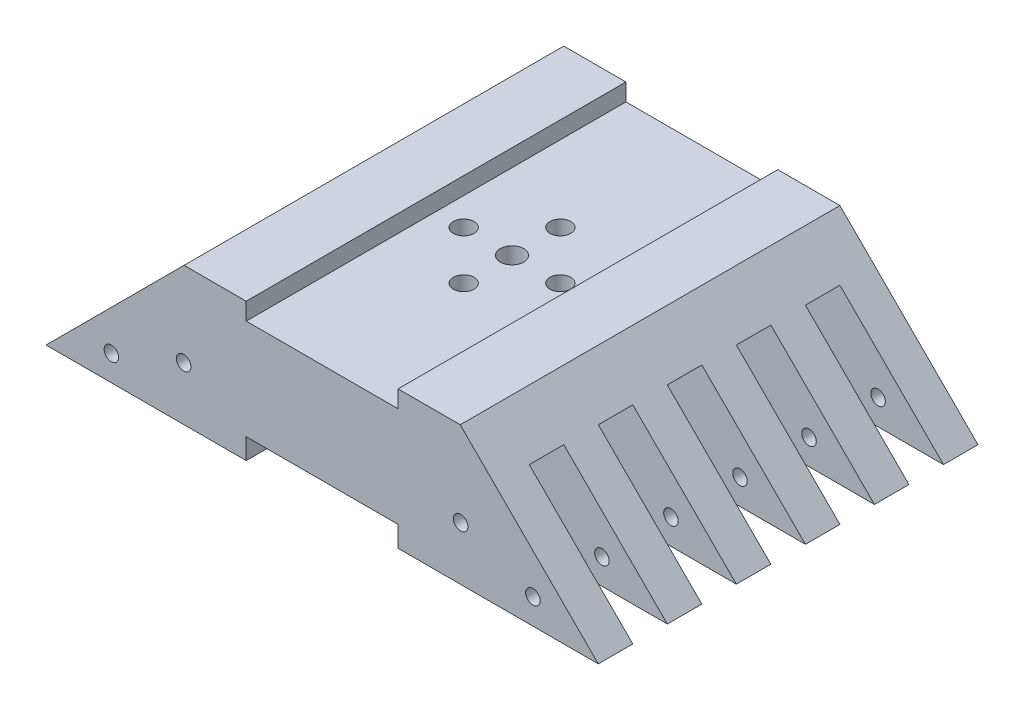
SolidWorks part; units mm, degrees
ref_plane "前视基准面" through (0, 0, 0) normal (0, 0, 1) x (1, 0, 0)
ref_plane "上视基准面" through (0, 0, 0) normal (0, 1, 0) x (1, 0, 0)
ref_plane "右视基准面" through (0, 0, 0) normal (1, 0, 0) x (0, 0, -1)
other "Configuration Table"
sketch "草图1" plane through (0, 0, 0) normal (0, 0, 1) x (1, 0, 0)
  line L0 (-20, 10) -> (20, 10)
  line L1 (-40, -10) -> (40, -10)
  line L2 (-20, 10) -> (-40, -10)
  line L3 (65.6627, -51.1176) -> (66.2035, -49.4794)
  line L4 (20, 10) -> (40, -10)
  line L5 (-11, 10) -> (-11, 7.5)
  line L6 (0, 10) -> (0, -10) construction
  line L7 (11, 10) -> (11, 7.5)
  line L8 (-11, 7.5) -> (11, 7.5)
  line L9 (-11, -10) -> (-11, -7)
  line L10 (11, -10) -> (11, -7)
  line L11 (-11, -7) -> (11, -7)
  line L12 (-20.0626, -2.2419) -> (-40, -10) construction
  circle A0 centre (0, 0) radius 10 construction
  circle A1 centre (-20.0626, -2.2419) radius 1.05
  circle A2 centre (-30.525, -6.3131) radius 1.05
  circle A3 centre (20.0626, -2.2419) radius 1.05
  circle A4 centre (30.525, -6.3131) radius 1.05
  point P6 (0, 10)
  point P9 (0, -10)
  point P29 (0, 0)
  point P30 (-30.525, -6.3131)
  dimension "D1" = 22
  dimension "D6" = 2.1
  dimension "D2" = 40
  dimension "D3" = 80
  dimension "D4" = 2.5
  dimension "D5" = 3
extrude "凸台-拉伸1" add sketch "草图1" along normal blind 55 contours L9 L11 L10 L1 L4 L0 L7 L8 L5 L2
sketch "草图2" plane through (0, -10, 0) normal (0, -1, 0) x (1, 0, 0)
  line L0 (-25.5, 45) -> (-25.5, 40)
  line L1 (-25.5, 55) -> (-25.5, 50)
  line L2 (-40, 55) -> (-11, 55) construction
  line L3 (-25.5, 35) -> (-25.5, 30)
  line L4 (-25.5, 25) -> (-25.5, 20)
  line L5 (-25.5, 15) -> (-25.5, 10)
  line L6 (-25.5, 5) -> (-25.5, 0)
  line L7 (40, 55) -> (40, 0) construction
  line L8 (-40, 55) -> (-40, 0) construction
  line L9 (40, 55) -> (40, 0)
  line L10 (-40, 55) -> (-40, 0)
  line L11 (-40, 50) -> (40, 50)
  line L12 (-40, 45) -> (40, 45)
  line L13 (-40, 40) -> (40, 40)
  line L14 (-40, 35) -> (40, 35)
  line L15 (-40, 30) -> (40, 30)
  line L16 (-40, 25) -> (40, 25)
  line L17 (-40, 20) -> (40, 20)
  line L18 (-40, 15) -> (40, 15)
  line L19 (-40, 10) -> (40, 10)
  line L20 (-40, 5) -> (40, 5)
  line M4 (-11, 0) -> (-11, 55)
  dimension "D1" = 6
  dimension "D2" = 10
extrude "切除-拉伸1" cut sketch "草图2" against normal blind 15 contours L10 L12 L11 M4 | L12 L9 L11 M4 | L10 L14 L13 M4 | L14 L9 L13 M4 | L10 L16 L15 M4 | L16 L9 L15 M4 | L10 L18 L17 M4 | L18 L9 L17 M4 | L10 L20 L19 M4 | L20 L9 L19 M4
sketch "草图3" plane through (0, 7.5, 0) normal (0, 1, 0) x (1, 0, 0)
  line L0 (0, 0) -> (0, -55)
  line L1 (-11, -55) -> (11, -55) construction
  circle A0 centre (0, -27.5) radius 7 construction
  circle A1 centre (0, -20.5) radius 1.5
  circle A2 centre (0, -27.5) radius 1.7
  circle A3 centre (7, -27.5) radius 1.5
  circle A4 centre (0, -34.5) radius 1.5
  circle A5 centre (-7, -27.5) radius 1.5
  point P19 (0, -27.5)
  dimension "D1" = 14
  dimension "D2" = 3
  dimension "D3" = 3.4
  dimension "D4" = 4
extrude "切除-拉伸2" cut sketch "草图3" against normal blind 15 contours L0 A1 | L0 A1 | L0 A2 | L0 A2 | A5 | A3 | L0 A4 | L0 A4
sketch "草图4" plane through (0, -7, 0) normal (0, -1, 0) x (1, 0, 0)
  line L1 (-10, 38.182) -> (10, 38.182)
  line L2 (-10, 38.182) -> (-10, 16.818)
  line L3 (-10, 16.818) -> (10, 16.818)
  line L4 (10, 38.182) -> (10, 16.818)
  line L5 (-10, 38.182) -> (10, 16.818) construction
  line L6 (-10, 16.818) -> (10, 38.182) construction
  point P0 (0, 27.5)
  dimension "D1" = 20
extrude "切除-拉伸3" cut sketch "草图4" against normal blind 12
